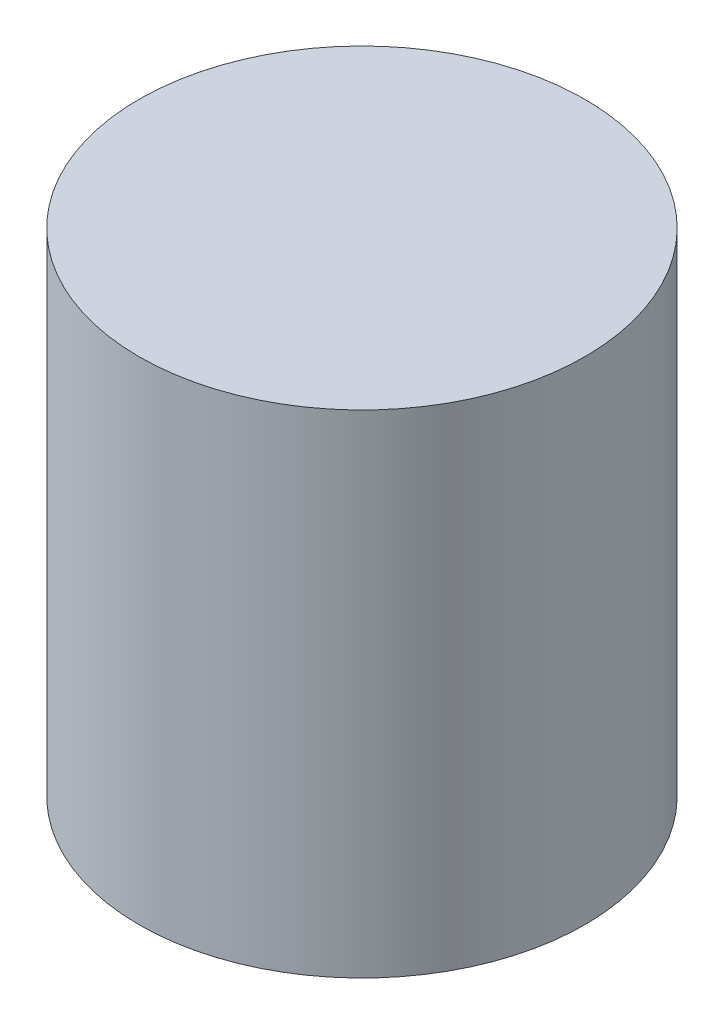
SolidWorks part; units mm, degrees
ref_plane "Piano frontale" through (0, 0, 0) normal (0, 0, 1) x (1, 0, 0)
ref_plane "Piano superiore" through (0, 0, 0) normal (0, 1, 0) x (1, 0, 0)
ref_plane "Piano destro" through (0, 0, 0) normal (1, 0, 0) x (0, 0, -1)
sketch "Schizzo1" plane through (0, 0, 0) normal (0, 1, 0) x (1, 0, 0)
  circle A0 centre (0, 0) radius 14.5
  dimension "D1" = 29
extrude "Estrusione-Estrusione1" add sketch "Schizzo1" along normal blind 32
